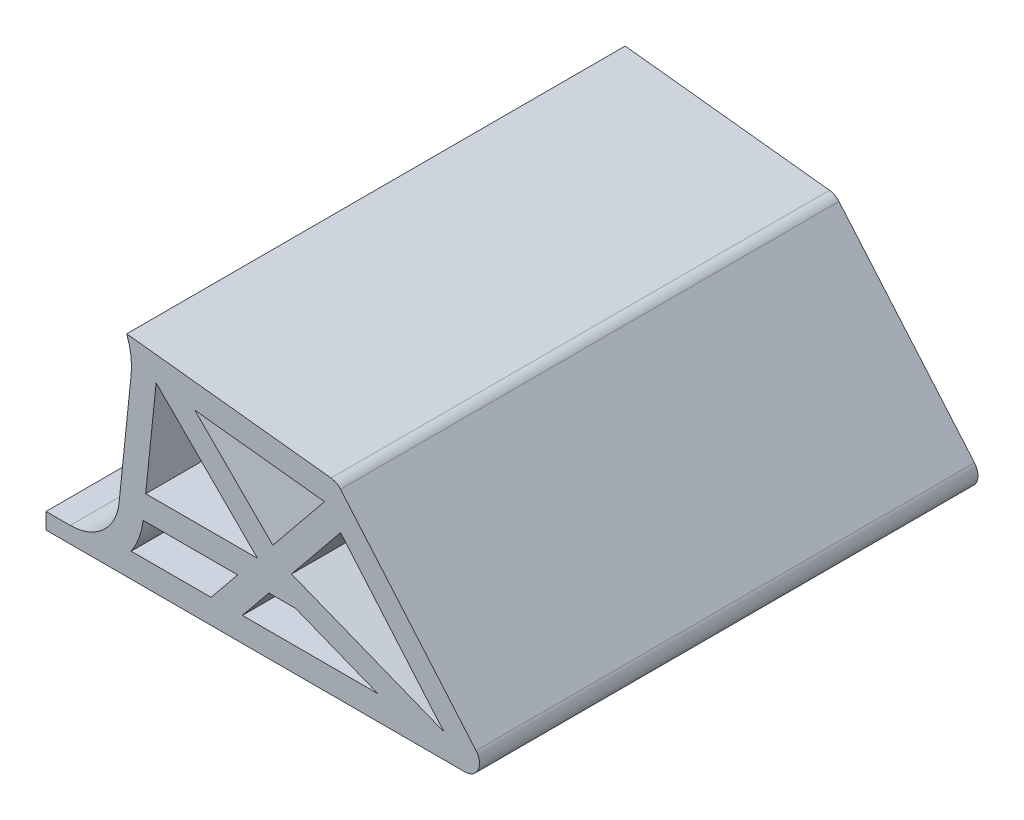
SolidWorks part; units mm, degrees
ref_plane "Front Plane" through (0, 0, 0) normal (0, 0, 1) x (1, 0, 0)
ref_plane "Top Plane" through (0, 0, 0) normal (0, 1, 0) x (1, 0, 0)
ref_plane "Right Plane" through (0, 0, 0) normal (1, 0, 0) x (0, 0, -1)
sketch "Sketch1" plane through (0, 0, 0) normal (0, 0, 1) x (1, 0, 0)
  line L0 (103.6807, 17.9269) -> (129.1142, -11.3363) construction
  line L1 (131.61, -14.208) -> (128.6112, -14.2939) construction
  line L2 (68.434, -16.017) -> (97.7418, 17.9091) construction
  line L4 (59.777, 19.097) -> (57.3034, -4.893) construction
  line L5 (59.8765, 19.0867) -> (57.4029, -4.9032)
  line L6 (128.6112, -14.2939) -> (131.61, -14.208) construction
  line L7 (100.71, 21.345) -> (100.71, 18.345) construction
  line L8 (58.9699, 26.0032) -> (101.0414, 21.3266)
  line L9 (130.8916, -12.3445) -> (102.9904, 20.2944)
  line L11 (47.3562, -13.8673) -> (36.6857, -13.8673) construction
  line L12 (47.3562, -13.9673) -> (42.3562, -13.9673)
  line L14 (38.3562, -17.2939) -> (38.3562, -14.8673) construction
  line L15 (42.3562, -17.2939) -> (42.3562, -13.9673)
  line L16 (42.3562, -17.2939) -> (128.6112, -17.2939)
  line L17 (42.3562, -17.2939) -> (42.3562, -14.8673) construction
  line L18 (100.71, 21.345) -> (103.6807, 17.9269) construction
  line L19 (97.7418, 17.9091) -> (100.71, 21.345) construction
  line L20 (128.6112, -14.2939) -> (125.6125, -14.3797) construction
  line L21 (125.6125, -14.3797) -> (68.434, -16.017) construction
  line L22 (129.1142, -11.3363) -> (131.61, -14.208) construction
  line L23 (42.3562, -13.9673) -> (36.6857, -13.9673) construction
  line L24 (47.3562, -13.9673) -> (36.6857, -13.9673) construction
  circle A0 centre (0, 0) radius 1.3578 construction
  arc A3 (48.0458, -13.8435) -> (57.3034, -4.893) centre (47.3562, -3.8673) ccw construction
  arc A4 (59.777, 19.097) -> (58.8764, 25.9676) centre (44.8562, 20.6355) ccw construction
  arc A5 (47.3562, -13.9673) -> (57.4029, -4.9032) centre (47.3562, -3.8673) ccw
  arc A6 (59.8765, 19.0867) -> (58.9699, 26.0032) centre (44.8562, 20.6355) ccw
  arc A7 (102.9904, 20.2944) -> (101.0414, 21.3266) centre (100.71, 18.345) ccw
  arc A8 (128.6112, -17.2939) -> (130.8916, -12.3445) centre (128.6112, -14.2939) ccw
  arc A9 (48.0527, -13.9433) -> (57.4029, -4.9032) centre (47.3562, -3.8673) ccw construction
  arc A10 (103.6807, 17.9269) -> (102.9904, 20.2944) centre (100.71, 18.345) ccw construction
  arc A11 (97.7418, 17.9091) -> (103.6807, 17.9269) centre (100.71, 18.345) ccw construction
  arc A12 (100.71, 21.345) -> (97.7418, 17.9091) centre (100.71, 18.345) ccw construction
  arc A13 (125.6125, -14.3797) -> (128.6112, -17.2939) centre (128.6112, -14.2939) ccw construction
  arc A14 (129.1142, -11.3363) -> (125.6125, -14.3797) centre (128.6112, -14.2939) ccw construction
  arc A15 (130.8916, -12.3445) -> (129.1142, -11.3363) centre (128.6112, -14.2939) ccw construction
  arc A16 (101.0414, 21.3266) -> (100.71, 21.345) centre (100.71, 18.345) ccw construction
  point P3 (100.71, 21.345)
  point P4 (131.61, -14.208)
  point P5 (68.434, -16.017)
  point P30 (100.71, 18.345)
  dimension "D8" = 6
  dimension "D9" = 6
  dimension "D1" = 68.434
  dimension "D2" = 131.61
  dimension "D3" = 100.71
  dimension "D4" = 21.345
  dimension "D5" = 16.017
  dimension "D6" = 14.208
  dimension "D7" = 0.1
  dimension "D10" = 0.1
  dimension "D11" = 4
extrude "Boss-Extrude1" add sketch "Sketch1" along normal mid plane 102.62
sketch "Sketch2" plane through (0, 0, 51.31) normal (0, 0, 1) x (1, 0, 0)
  line L0 (42.3562, -17.2939) -> (128.6112, -17.2939) construction
  line L1 (130.8916, -12.3445) -> (102.9904, 20.2944) construction
  line L2 (101.0414, 21.3266) -> (58.9699, 26.0032) construction
  line L3 (59.8765, 19.0867) -> (57.4029, -4.9032) construction
  line L4 (42.3562, -17.2939) -> (54.2654, -17.2939) construction
  line L5 (130.8916, -12.3445) -> (102.9904, 20.2944) construction
  line L6 (101.0414, 21.3266) -> (58.9699, 26.0032) construction
  line L7 (59.8765, 19.0867) -> (57.4029, -4.9032) construction
  line L8 (65.028, 20.299) -> (62.3765, -5.4161)
  line L9 (99.7034, 16.4446) -> (65.028, 20.299)
  line L10 (124.2704, -12.2939) -> (99.7034, 16.4446)
  line L11 (42.3562, -12.2939) -> (52.9242, -12.2939) construction
  line L12 (54.2654, -17.2939) -> (128.6112, -17.2939) construction
  line L13 (42.3562, -17.2939) -> (128.6112, -17.2939) construction
  line L14 (52.9242, -12.2939) -> (59.8862, -12.2939) construction
  line L15 (59.8862, -12.2939) -> (124.2704, -12.2939)
  line L16 (42.3562, -12.2939) -> (128.6112, -12.2939) construction
  line L17 (100.489, 16.3572) -> (99.7034, 16.4446) construction
  line L18 (100.489, 16.3572) -> (58.4175, 21.0338) construction
  line L19 (99.7034, 16.4446) -> (99.1898, 17.0454) construction
  line L20 (127.091, -15.5934) -> (99.1898, 17.0454) construction
  line L21 (124.2704, -12.2939) -> (128.6112, -12.2939) construction
  line L22 (127.091, -15.5934) -> (124.2704, -12.2939) construction
  line L23 (64.8501, 18.5739) -> (62.3765, -5.4161) construction
  line L24 (65.028, 20.299) -> (58.4175, 21.0338) construction
  arc A0 (47.3562, -13.9673) -> (57.4029, -4.9032) centre (47.3562, -3.8673) ccw construction
  arc A1 (52.9242, -12.2939) -> (57.4029, -4.9032) centre (47.3562, -3.8673) ccw construction
  arc A2 (47.3562, -18.9673) -> (54.2654, -17.2939) centre (47.3562, -3.8673) ccw construction
  arc A3 (54.2654, -17.2939) -> (59.8862, -12.2939) centre (47.3562, -3.8673) ccw construction
  arc A4 (59.8862, -12.2939) -> (62.3765, -5.4161) centre (47.3562, -3.8673) ccw
  arc A5 (47.3562, -18.9673) -> (62.3765, -5.4161) centre (47.3562, -3.8673) ccw construction
  arc A6 (47.3562, -13.9673) -> (52.9242, -12.2939) centre (47.3562, -3.8673) ccw construction
  arc A7 (47.3562, -13.9673) -> (57.4029, -4.9032) centre (47.3562, -3.8673) ccw construction
  dimension "D1" = 5
extrude "Cut-Extrude1" cut sketch "Sketch2" against normal through all
sketch "Sketch3" plane through (0, 0, 0) normal (0, 0, 1) x (1, 0, 0)
  line L0 (65.028, 20.299) -> (62.3765, -5.4161) construction
  line L1 (99.7034, 16.4446) -> (65.028, 20.299) construction
  line L2 (124.2704, -12.2939) -> (99.7034, 16.4446) construction
  line L3 (59.8862, -12.2939) -> (124.2704, -12.2939) construction
  line L4 (59.8862, -12.2939) -> (124.2704, -12.2939) construction
  line L5 (124.2704, -12.2939) -> (99.7034, 16.4446) construction
  line L6 (99.7034, 16.4446) -> (65.028, 20.299) construction
  line L7 (65.028, 20.299) -> (62.3765, -5.4161) construction
  line L8 (99.7034, 16.4446) -> (76.3375, -12.2939)
  line L9 (124.2704, -12.2939) -> (88.0204, 2.0754)
  line L10 (65.028, 20.299) -> (85.8819, -0.5549)
  line L11 (85.8819, -0.5549) -> (62.8778, -0.5549)
  line L12 (62.8778, -0.5549) -> (59.8862, -0.5549)
  arc A0 (59.8862, -12.2939) -> (62.3765, -5.4161) centre (47.3562, -3.8673) ccw construction
  arc A1 (59.8862, -12.2939) -> (62.3765, -5.4161) centre (47.3562, -3.8673) ccw construction
  dimension "D1" = 38.657
  dimension "D2" = 11.739
extrude "Extrude-Thin1" add sketch "Sketch3" along normal up to surface and the other way up to surface thin
equation "\"D9@Sketch1\"=\"D8@Sketch1\""
